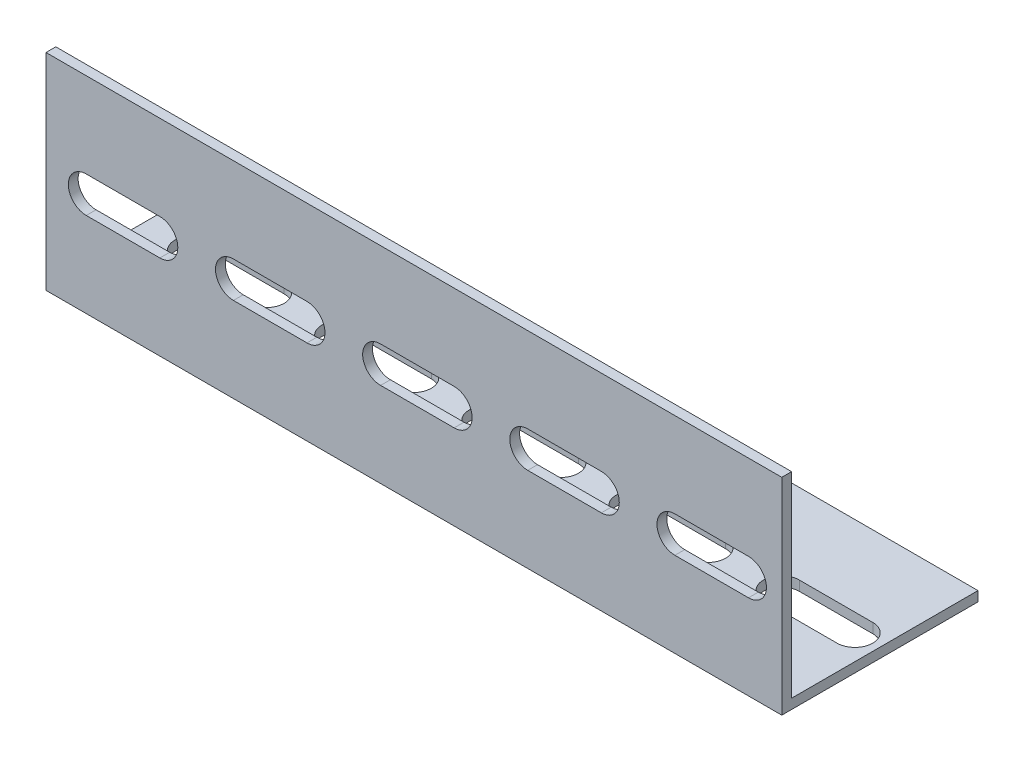
SolidWorks part; units mm, degrees
ref_plane "Front Plane" through (0, 0, 0) normal (0, 0, 1) x (1, 0, 0)
ref_plane "Top Plane" through (0, 0, 0) normal (0, 1, 0) x (1, 0, 0)
ref_plane "Right Plane" through (0, 0, 0) normal (1, 0, 0) x (0, 0, -1)
sketch "Sketch1" plane through (0, 0, 0) normal (0, 1, 0) x (1, 0, 0)
  line L1 (-75, 20) -> (75, 20)
  line L2 (-75, 20) -> (-75, -20)
  line L3 (-75, -20) -> (75, -20)
  line L4 (75, 20) -> (75, -20)
  line L5 (-75, 20) -> (75, -20) construction
  line L6 (-75, -20) -> (75, 20) construction
  point P0 (0, 0)
  dimension "D1" = 150
  dimension "D2" = 40
extrude "Boss-Extrude1" add sketch "Sketch1" along normal blind 2
sketch "Sketch2" plane through (0, 2, 0) normal (0, 1, 0) x (1, 0, 0)
  line L0 (75, -20) -> (75, 20) construction
  line L1 (-75, -20) -> (75, -20)
  line L2 (-75, -20) -> (-75, -18)
  line L3 (-75, -18) -> (75, -18)
  line L4 (75, -20) -> (75, -18)
  dimension "D1" = 2
extrude "Boss-Extrude2" add sketch "Sketch2" along normal blind 40
sketch "Sketch3" plane through (0, 0, 20) normal (0, 0, 1) x (1, 0, 0)
  line L0 (-36.789, 24.6488) -> (-21.789, 24.6488)
  line L1 (-66.789, 24.6488) -> (-51.789, 24.6488)
  line L3 (-66.789, 17.3313) -> (-51.789, 17.3313)
  line L5 (-66.789, 24.6488) -> (-51.789, 17.3313) construction
  line L6 (-66.789, 17.3313) -> (-51.789, 24.6488) construction
  line L7 (-36.789, 17.3313) -> (-21.789, 17.3313)
  line L8 (-6.789, 24.6488) -> (8.211, 24.6488)
  line L9 (-6.789, 17.3313) -> (8.211, 17.3313)
  line L10 (23.211, 24.6488) -> (38.211, 24.6488)
  line L11 (23.211, 17.3313) -> (38.211, 17.3313)
  line L12 (53.211, 24.6488) -> (68.211, 24.6488)
  line L13 (53.211, 17.3313) -> (68.211, 17.3313)
  arc A0 (-51.789, 24.6488) -> (-51.789, 17.3313) centre (-51.789, 20.99) cw
  arc A1 (-66.789, 24.6488) -> (-66.789, 17.3313) centre (-66.789, 20.99) ccw
  arc A2 (-21.789, 24.6488) -> (-21.789, 17.3313) centre (-21.789, 20.99) cw
  arc A3 (-36.789, 24.6488) -> (-36.789, 17.3313) centre (-36.789, 20.99) ccw
  arc A4 (8.211, 24.6488) -> (8.211, 17.3313) centre (8.211, 20.99) cw
  arc A5 (-6.789, 24.6488) -> (-6.789, 17.3313) centre (-6.789, 20.99) ccw
  arc A6 (38.211, 24.6488) -> (38.211, 17.3313) centre (38.211, 20.99) cw
  arc A7 (23.211, 24.6488) -> (23.211, 17.3313) centre (23.211, 20.99) ccw
  arc A8 (68.211, 24.6488) -> (68.211, 17.3313) centre (68.211, 20.99) cw
  arc A9 (53.211, 24.6488) -> (53.211, 17.3313) centre (53.211, 20.99) ccw
  point P0 (-59.289, 20.99)
  dimension "D1" = 15
  dimension "D3" = 7.3176
  dimension "D2" = 5
extrude "Cut-Extrude2" cut sketch "Sketch3" against normal blind 10
sketch "Sketch4" plane through (0, 0, 0) normal (0, -1, 0) x (1, 0, 0)
  line L0 (-35.09, 3.65) -> (-20.09, 3.65)
  line L1 (-65.09, 3.65) -> (-50.09, 3.65)
  line L3 (-65.09, -3.65) -> (-50.09, -3.65)
  line L5 (-65.09, 3.65) -> (-50.09, -3.65) construction
  line L6 (-65.09, -3.65) -> (-50.09, 3.65) construction
  line L7 (-35.09, -3.65) -> (-20.09, -3.65)
  line L8 (-5.09, 3.65) -> (9.91, 3.65)
  line L9 (-5.09, -3.65) -> (9.91, -3.65)
  line L10 (24.91, 3.65) -> (39.91, 3.65)
  line L11 (24.91, -3.65) -> (39.91, -3.65)
  line L12 (54.91, 3.65) -> (69.91, 3.65)
  line L13 (54.91, -3.65) -> (69.91, -3.65)
  arc A0 (-65.09, 3.65) -> (-65.09, -3.65) centre (-65.09, 0) ccw
  arc A1 (-50.09, 3.65) -> (-50.09, -3.65) centre (-50.09, 0) cw
  arc A2 (-20.09, 3.65) -> (-20.09, -3.65) centre (-20.09, 0) cw
  arc A3 (-35.09, 3.65) -> (-35.09, -3.65) centre (-35.09, 0) ccw
  arc A4 (9.91, 3.65) -> (9.91, -3.65) centre (9.91, 0) cw
  arc A5 (-5.09, 3.65) -> (-5.09, -3.65) centre (-5.09, 0) ccw
  arc A6 (39.91, 3.65) -> (39.91, -3.65) centre (39.91, 0) cw
  arc A7 (24.91, 3.65) -> (24.91, -3.65) centre (24.91, 0) ccw
  arc A8 (69.91, 3.65) -> (69.91, -3.65) centre (69.91, 0) cw
  arc A9 (54.91, 3.65) -> (54.91, -3.65) centre (54.91, 0) ccw
  point P0 (-57.59, 0)
  dimension "D1" = 15
  dimension "D2" = 5
extrude "Cut-Extrude4" cut sketch "Sketch4" against normal blind 10
